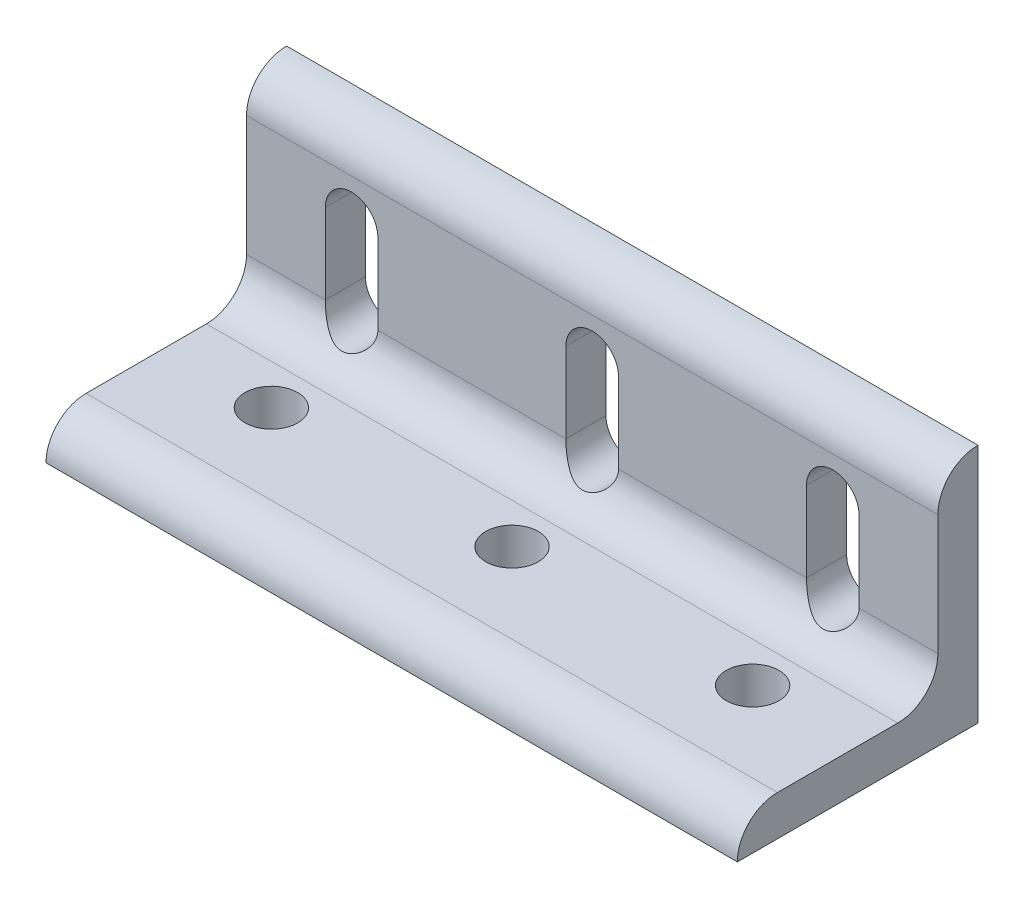
SolidWorks part; units mm, degrees
ref_plane "Front"
ref_plane "Top" through (0, 0, 0) normal (0, 1, 0) x (1, 0, 0)
ref_plane "Right" through (0, 0, 0) normal (1, 0, 0) x (0, 0, -1)
sketch "Sketch1" plane through (0, 0, 0) normal (1, 0, 0) x (0, 0, -1)
  line L0 (-6.35, 12.7) -> (-6.35, 31.75)
  line L1 (-31.75, 6.35) -> (-12.7, 6.35)
  line L6 (0, 0) -> (0, 38.1)
  line L7 (-38.1, 0) -> (0, 0)
  arc A0 (-12.7, 6.35) -> (-6.35, 12.7) centre (-12.7, 12.7) ccw
  arc A1 (0, 38.1) -> (-6.35, 31.75) centre (0, 31.75) ccw
  arc A2 (-31.75, 6.35) -> (-38.1, 0) centre (-31.75, 0) ccw
  dimension "InnerRadius" = 6.35
  dimension "LengthZ" = 38.1
  dimension "HeightY" = 38.1
  dimension "Thick" = 6.35
extrude "Base Extrude" add sketch "Sketch1" against normal mid plane 109.474
sketch "Sketch2" plane through (0, 0, 0) normal (0, -1, 0) x (1, 0, 0)
  line L0 (-54.737, 0) -> (54.737, 0) construction
  line L1 (-54.737, 38.1) -> (-54.737, 0) construction
  circle A1 centre (-38.1, 19.05) radius 4.1656
  dimension "HoleDiam" = 8.3312
  dimension "HoleZ" = 19.05
  dimension "HoleX" = 16.637
extrude "Hole" cut sketch "Sketch2" against normal through all
pattern_linear "Hole Pattern"
sketch "Sketch3" plane through (0, 0, 0) normal (0, 0, -1) x (-1, 0, 0)
  line L0 (54.737, 0) -> (-54.737, 0) construction
  line L1 (54.737, 0) -> (54.737, 38.1) construction
  line L3 (42.2656, 25.4) -> (42.2656, 12.7)
  line L4 (33.9344, 12.7) -> (33.9344, 25.4)
  arc A0 (33.9344, 12.7) -> (42.2656, 12.7) centre (38.1, 12.7) ccw
  arc A1 (42.2656, 25.4) -> (33.9344, 25.4) centre (38.1, 25.4) ccw
  dimension "SlotWidth" = 8.3312
  dimension "SlotY" = 12.7
  dimension "SlotX" = 16.637
  dimension "SlotLength" = 21.0312
extrude "Slot" cut sketch "Sketch3" against normal through all
pattern_linear "Slot Pattern"
